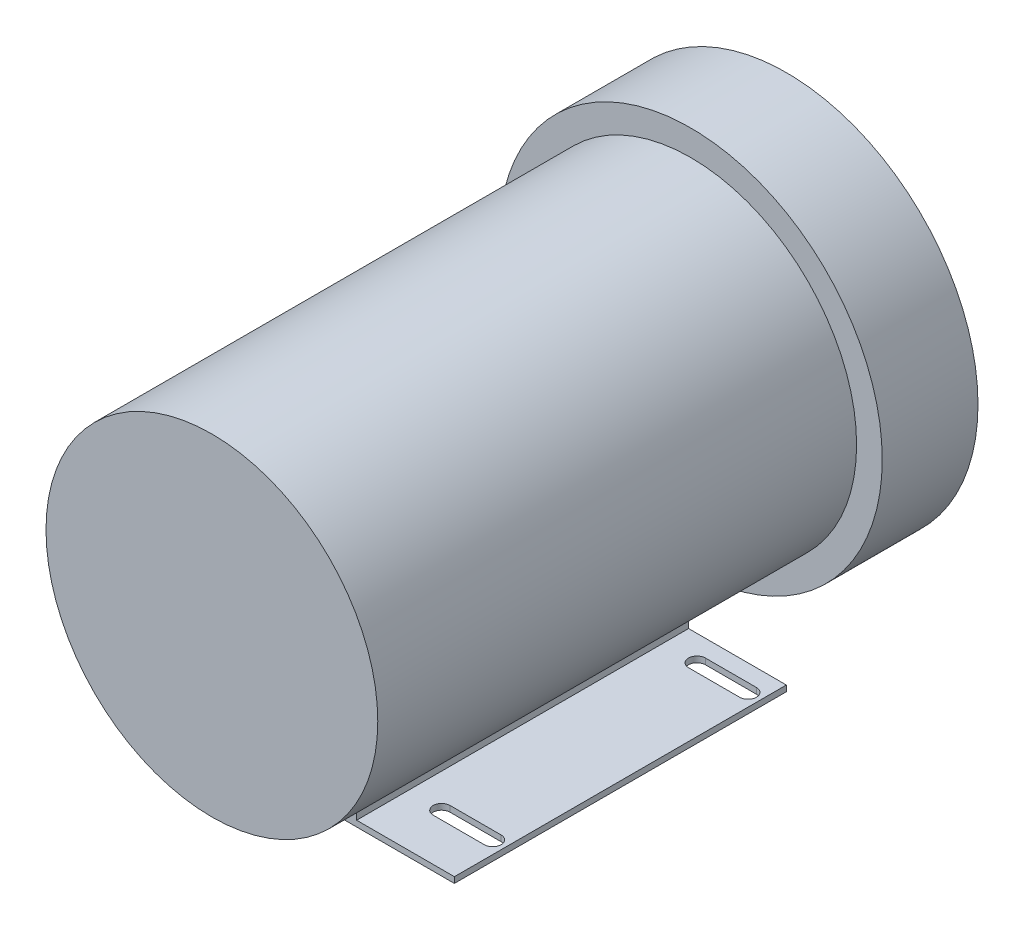
SolidWorks part; units mm, degrees
ref_plane "Front" through (0, 0, 0) normal (0, 0, 1) x (1, 0, 0)
ref_plane "Top" through (0, 0, 0) normal (0, 1, 0) x (1, 0, 0)
ref_plane "Right" through (0, 0, 0) normal (1, 0, 0) x (0, 0, -1)
sketch "Sketch1" plane through (0, 0, 0) normal (0, 0, 1) x (1, 0, 0)
  circle A0 centre (0, 0) radius 82.4992
  dimension "D1" = 164.9984
extrude "Boss-Extrude1" add sketch "Sketch1" against normal blind 285.75
sketch "Sketch2" plane through (0, 0, -285.75) normal (0, 0, -1) x (-1, 0, 0)
  circle A0 centre (0, 0) radius 95.25
  dimension "D1" = 190.5
extrude "Boss-Extrude2" add sketch "Sketch2" against normal blind 47.625
ref_plane "Plane1" through (0, 0, -38.1) normal (0, 0, 1) x (1, 0, 0)
sketch "Sketch3" plane through (0, 0, -38.1) normal (0, 0, 1) x (1, 0, 0)
  line L0 (-82.4992, 0) -> (-82.4992, -88.9) construction
  line L1 (82.4992, -88.9) -> (-82.4992, -88.9)
  line L2 (82.4992, -88.9) -> (82.4992, -85.979)
  line L3 (82.4992, -85.979) -> (-82.4992, -85.979)
  line L4 (-82.4992, -88.9) -> (-82.4992, -85.979)
  line L5 (82.4992, -88.9) -> (-82.4992, -85.979) construction
  line L6 (82.4992, -85.979) -> (-82.4992, -88.9) construction
  line L7 (82.4992, 0) -> (82.4992, -86.898) construction
  line L8 (33.8736, -75.2243) -> (33.8736, -85.979)
  line L9 (0, 0) -> (0, -88.9) construction
  line L10 (-33.8736, -75.2243) -> (-33.8736, -85.979)
  circle A0 centre (0, 0) radius 82.4992 construction
  circle A1 centre (0, 0) radius 82.4992 construction
  arc A2 (82.4992, 0) -> (-82.4992, 0) centre (0, 0) ccw
  arc A3 (-33.8736, -75.2243) -> (33.8736, -75.2243) centre (0, 0) ccw
  point P4 (0, -87.4395)
  dimension "D1" = 88.9
  dimension "D2" = 2.921
extrude "Boss-Extrude3" add sketch "Sketch3" against normal blind 165.1 contours A3 L10 L3 L8 | L4 L1 L2 L3
sketch "Sketch4" plane through (0, -85.979, 0) normal (0, 1, 0) x (1, 0, 0)
  line L0 (-76.1492, 63.5) -> (-50.7492, 63.5) construction
  line L1 (-76.1492, 67.691) -> (-50.7492, 67.691)
  line L2 (-76.1492, 59.309) -> (-50.7492, 59.309)
  line L3 (-90.7491, 38.1) -> (90.7491, 38.1) construction
  line L4 (-82.4992, 203.2) -> (-82.4992, 38.1) construction
  line L5 (-50.7492, 190.5) -> (-76.1492, 190.5) construction
  line L6 (-50.7492, 186.309) -> (-76.1492, 186.309)
  line L7 (-50.7492, 194.691) -> (-76.1492, 194.691)
  line L8 (-33.8736, 203.2) -> (-82.4992, 203.2) construction
  arc A0 (-76.1492, 67.691) -> (-76.1492, 59.309) centre (-76.1492, 63.5) ccw
  arc A1 (-50.7492, 59.309) -> (-50.7492, 67.691) centre (-50.7492, 63.5) ccw
  arc A2 (-50.7492, 186.309) -> (-50.7492, 194.691) centre (-50.7492, 190.5) ccw
  arc A3 (-76.1492, 194.691) -> (-76.1492, 186.309) centre (-76.1492, 190.5) ccw
  point P2 (-63.4492, 63.5)
  point P13 (-63.4492, 190.5)
  dimension "D6" = 6.35
  dimension "D1" = 25.4
  dimension "D2" = 6.35
  dimension "D3" = 8.382
  dimension "D4" = 25.4
  dimension "D5" = 12.7
  dimension "D7" = 8.382
extrude "Cut-Extrude1" cut sketch "Sketch4" against normal up to next
mirror "Mirror1" about plane through (0, 0, 0) normal (1, 0, 0) of "Cut-Extrude1"
